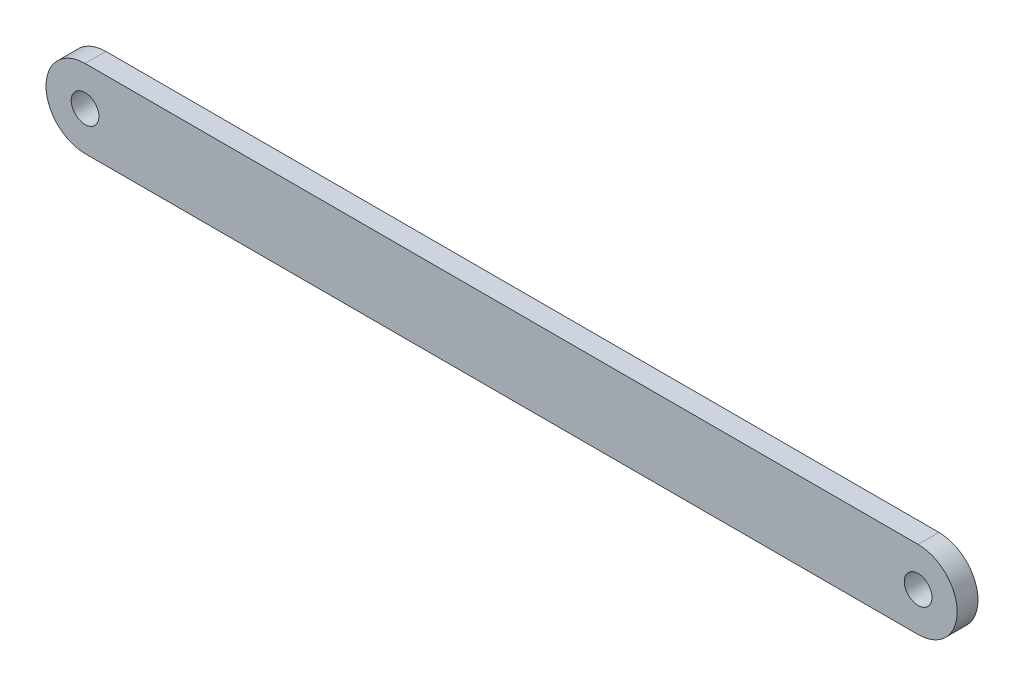
SolidWorks part; units mm, degrees
ref_plane "Front Plane" through (0, 0, 0) normal (0, 0, 1) x (1, 0, 0)
ref_plane "Top Plane" through (0, 0, 0) normal (0, 1, 0) x (1, 0, 0)
ref_plane "Right Plane" through (0, 0, 0) normal (1, 0, 0) x (0, 0, -1)
sketch "Sketch1" plane through (0, 0, 0) normal (0, 0, 1) x (1, 0, 0)
  line L0 (-101.6, 0) -> (101.6, 0) construction
  line L1 (-101.6, 9.525) -> (101.6, 9.525)
  line L2 (-101.6, -9.525) -> (101.6, -9.525)
  arc A0 (-101.6, 9.525) -> (-101.6, -9.525) centre (-101.6, 0) ccw
  arc A1 (101.6, -9.525) -> (101.6, 9.525) centre (101.6, 0) ccw
  circle A2 centre (-101.6, 0) radius 3.3782
  circle A3 centre (101.6, 0) radius 3.3782
  point P2 (0, 0)
  dimension "D2" = 6.7564
  dimension "D3" = 9.525
  dimension "D1" = 203.2
extrude "Boss-Extrude1" add sketch "Sketch1" along normal blind 5.08
